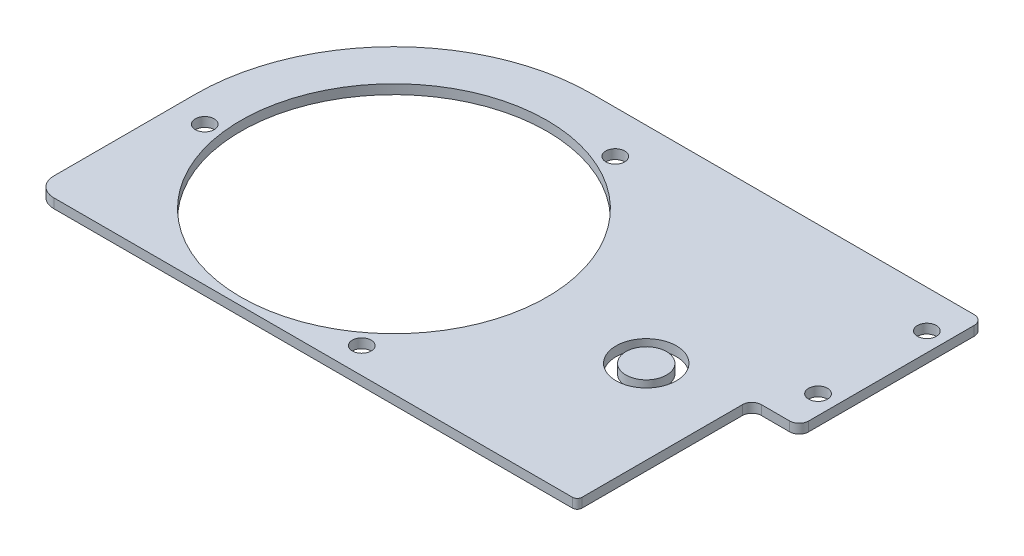
SolidWorks part; units mm, degrees
ref_plane "Front Plane" through (0, 0, 0) normal (0, 0, 1) x (1, 0, 0)
ref_plane "Top Plane" through (0, 0, 0) normal (0, 1, 0) x (1, 0, 0)
ref_plane "Right Plane" through (0, 0, 0) normal (1, 0, 0) x (0, 0, -1)
sketch "Sketch1" plane through (0, 0, 0) normal (0, 1, 0) x (1, 0, 0)
  line L0 (0, 114.3) -> (0, -101.6) construction
  line L1 (256.5211, 133.3689) -> (0, 133.3689)
  line L2 (262.8711, 127.0189) -> (262.8711, 15.8008)
  line L3 (227.9555, -107.9311) -> (-120.6689, -107.9311)
  line L4 (-133.3689, 0) -> (-133.3689, -95.2311)
  line L5 (237.4711, 9.4508) -> (256.5211, 9.4508)
  line L6 (250.1711, 9.4508) -> (250.1711, 133.3689) construction
  line L7 (0, 0) -> (-133.3689, 0) construction
  line L8 (0, 0) -> (-133.3689, -3.0078) construction
  line L11 (231.1211, -104.7655) -> (231.1211, 3.1008)
  circle A0 centre (0, 0) radius 102.87
  circle A1 centre (0, 0) radius 114.3 construction
  circle A2 centre (-112.7386, -14.375) radius 6.35
  arc A3 (237.4711, 9.4508) -> (231.1211, 3.1008) centre (237.4711, 3.1008) ccw
  arc A4 (-133.3689, 0) -> (0, 133.3689) centre (0, 0) cw
  circle A5 centre (43.9202, 104.822) radius 6.35
  circle A6 centre (68.8184, -90.447) radius 6.35
  arc A7 (-120.6689, -107.9311) -> (-133.3689, -95.2311) centre (-120.6689, -95.2311) cw
  arc A8 (227.9555, -107.9311) -> (231.1211, -104.7655) centre (227.9555, -104.7655) ccw
  arc A9 (262.8711, 15.8008) -> (256.5211, 9.4508) centre (256.5211, 15.8008) cw
  arc A10 (256.5211, 133.3689) -> (262.8711, 127.0189) centre (256.5211, 127.0189) cw
  circle A11 centre (250.1711, 107.9689) radius 6.35
  circle A12 centre (250.1711, 34.8508) radius 6.35
  circle A13 centre (-112.7386, -14.375) radius 6.35 construction
  point P0 (0, 0)
  point P11 (0, 0)
  point P12 (246.9961, 9.4508)
  point P32 (231.1211, -107.9311)
  point P46 (0, 0)
  dimension "D3" = 205.74
  dimension "D5" = 228.6
  dimension "D6" = 12.7
  dimension "D7" = 123.9181
  dimension "D8" = 133.3689
  dimension "D11" = 31.75
  dimension "D12" = 25.4
  dimension "D14" = 12.7
  dimension "D9" = 6.35
  dimension "D10" = 12.7
  dimension "D2" = 117.3819
  dimension "D4" = 113.6514
  dimension "D13" = 12.7
  dimension "D15" = 25.4
  dimension "D16" = 396.24
  dimension "D17" = 3
extrude "Boss-Extrude1" add sketch "Sketch1" along normal blind 6.35
sketch "Sketch3" plane through (0, 6.35, 0) normal (0, 1, 0) x (1, 0, 0)
  line L0 (73.0061, 133.3689) -> (73.0061, -107.9311) construction
  line L5 (382.3904, 12.7189) -> (-202.4477, 12.7189) construction
  line L6 (333.3561, -152.3811) -> (-187.3439, -152.3811)
  line L7 (333.3561, -152.3811) -> (333.3561, 177.8189)
  line L8 (333.3561, 177.8189) -> (-187.3439, 177.8189)
  line L9 (-187.3439, -152.3811) -> (-187.3439, 177.8189)
  line L10 (333.3561, -152.3811) -> (-187.3439, 177.8189) construction
  line L11 (333.3561, 177.8189) -> (-187.3439, -152.3811) construction
  line L26 (262.8711, 15.8008) -> (262.8711, 127.0189) construction
  line L27 (-133.3689, 0) -> (-133.3689, -95.2311) construction
  line L28 (-120.6689, -107.9311) -> (227.9555, -107.9311) construction
  line L29 (256.5211, 133.3689) -> (0, 133.3689) construction
  line L30 (262.8711, 15.8008) -> (262.8711, 127.0189)
  line L31 (-133.3689, 0) -> (-133.3689, -95.2311)
  line L32 (-120.6689, -107.9311) -> (227.9555, -107.9311)
  line L33 (256.5211, 133.3689) -> (0, 133.3689)
  point P1 (73.0061, 12.7189)
  dimension "D1" = 520.7
  dimension "D2" = 206.375
  dimension "D3" = 330.2
  dimension "D4" = 120.65
  dimension "D7" = 396.24
  dimension "D8" = 241.3
sketch "Sketch5" plane through (0, 0, 0) normal (0, 1, 0) x (1, 0, 0)
  circle A1 centre (162.3238, 0) radius 11.176 construction
sketch "Sketch6" plane through (0, 0, 0) normal (0, 1, 0) x (1, 0, 0)
  circle A0 centre (174.7387, -5.1895) radius 20.32
  circle A2 centre (174.7387, -5.1895) radius 13.6394
  circle A3 centre (174.7387, -5.1895) radius 11.176 construction
  circle A4 centre (174.7387, -5.1895) radius 11.176 construction
  dimension "D1" = 40.64
extrude "Cut-Extrude1" cut sketch "Sketch6" along normal blind 28.448
